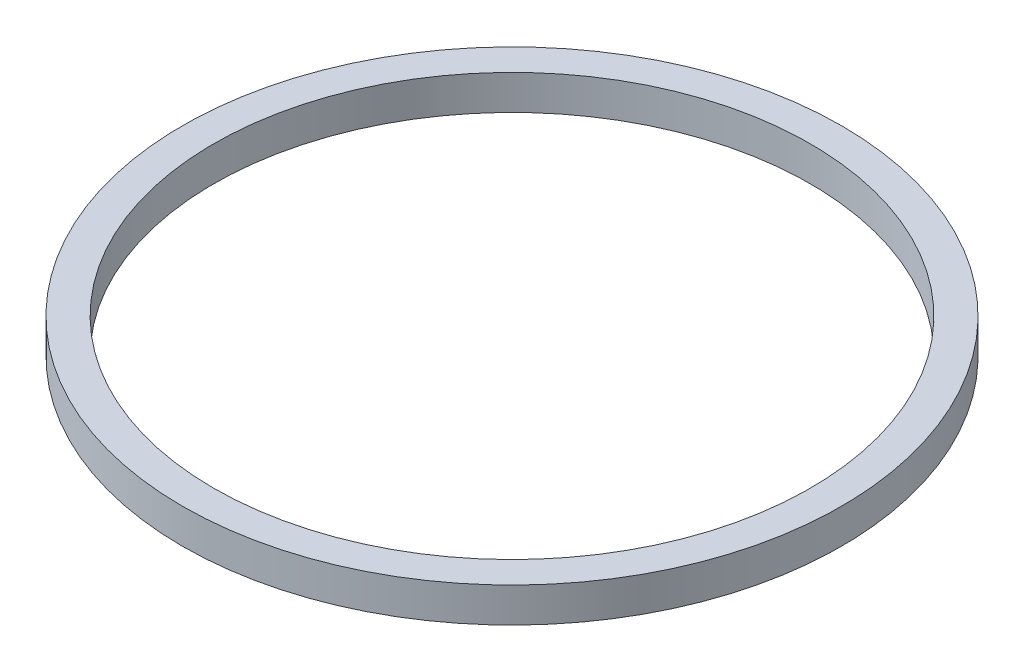
SolidWorks part; units mm, degrees
ref_plane "前视基准面" through (0, 0, 0) normal (0, 0, 1) x (1, 0, 0)
ref_plane "上视基准面" through (0, 0, 0) normal (0, 1, 0) x (1, 0, 0)
ref_plane "右视基准面" through (0, 0, 0) normal (1, 0, 0) x (0, 0, -1)
other "Configuration Table"
sketch "草图1" plane through (0, 0, 0) normal (0, 1, 0) x (1, 0, 0)
  circle A0 centre (0, 0) radius 8.6
  circle A1 centre (0, 0) radius 9.5
  dimension "D1" = 17.2
  dimension "D2" = 19
extrude "凸台-拉伸1" add sketch "草图1" along normal blind 1
